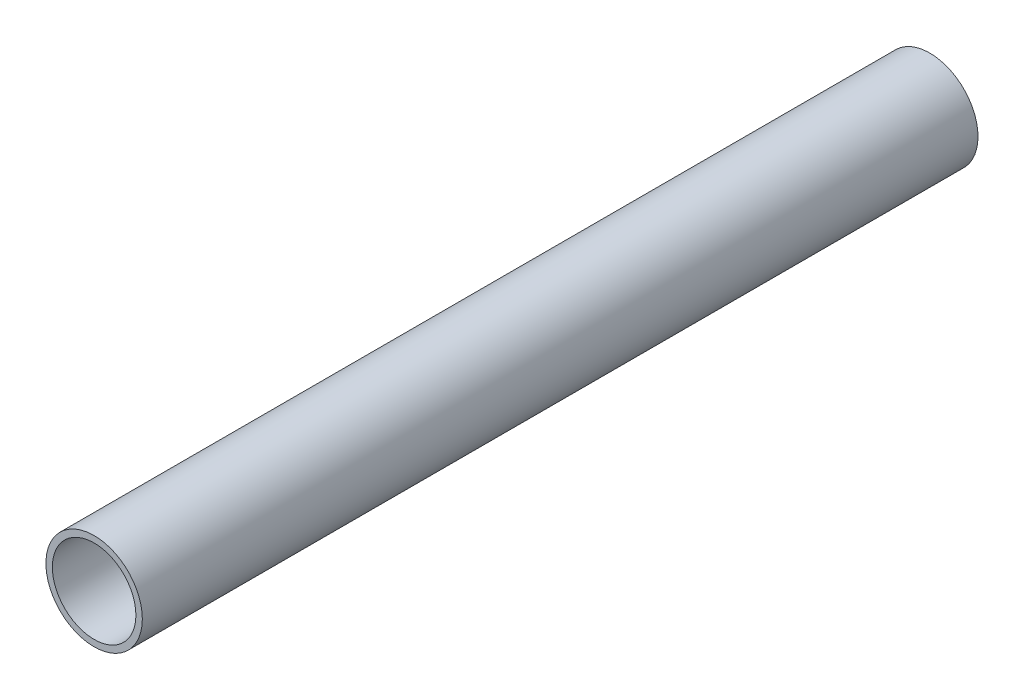
SolidWorks part; units mm, degrees
ref_plane "前视基准面" through (0, 0, 0) normal (0, 0, 1) x (1, 0, 0)
ref_plane "上视基准面" through (0, 0, 0) normal (0, 1, 0) x (1, 0, 0)
ref_plane "右视基准面" through (0, 0, 0) normal (1, 0, 0) x (0, 0, -1)
sketch "草图1" plane through (0, 0, 0) normal (0, 0, 1) x (1, 0, 0)
  circle A0 centre (0, 0) radius 15
  circle A1 centre (0, 0) radius 13
extrude "凸台-拉伸1" add sketch "草图1" along normal blind 260
